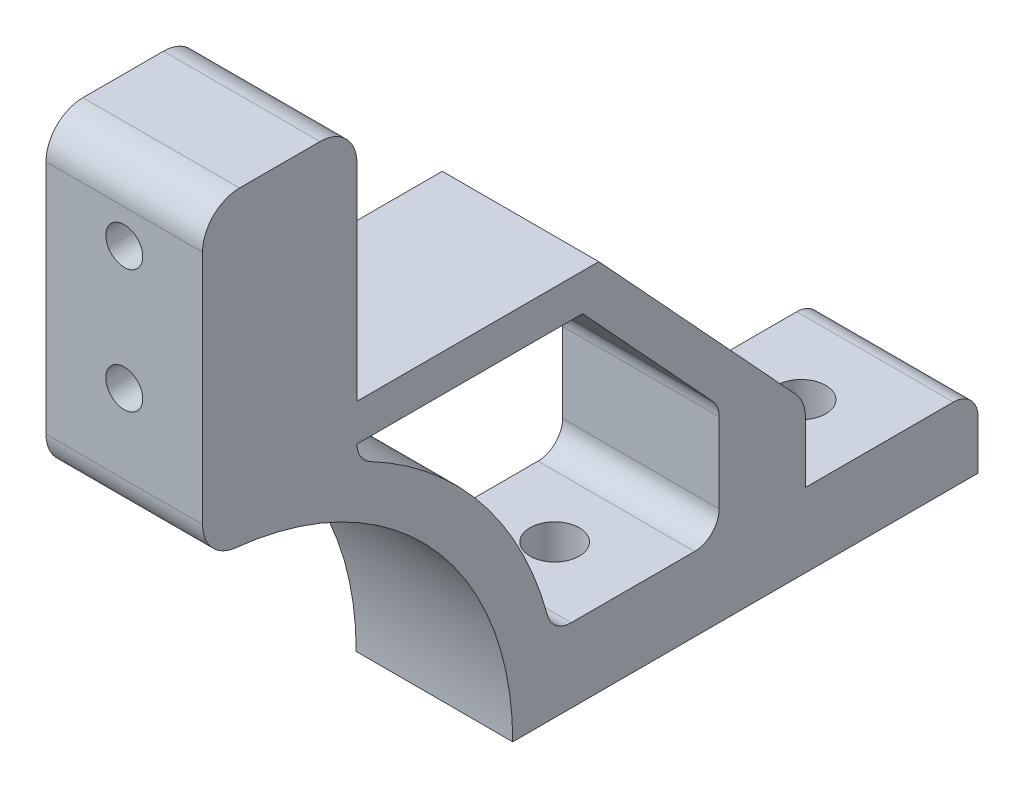
SolidWorks part; units mm, degrees
ref_plane "Front Plane" through (0, 0, 0) normal (0, 0, 1) x (1, 0, 0)
ref_plane "Top Plane" through (0, 0, 0) normal (0, 1, 0) x (1, 0, 0)
ref_plane "Right Plane" through (0, 0, 0) normal (1, 0, 0) x (0, 0, -1)
sketch "Sketch1" plane through (0, 0, 0) normal (1, 0, 0) x (0, 0, -1)
  line L0 (49.2041, 10.9568) -> (33.2349, 28.2516)
  line L3 (4.0847, 48) -> (10.6144, 48)
  line L4 (50, 4.0009) -> (50, 8.9217)
  line L11 (50, 4.0009) -> (62, 4.0009)
  line L16 (64, 2.0009) -> (64, -1.9991)
  line L18 (26.2541, -1.9991) -> (64, -1.9991)
  line L19 (42.4694, 13.8283) -> (31.9216, 25.2516)
  line L20 (13.6144, 39.9642) -> (13.6144, 28.2516)
  line L21 (43, 12.4715) -> (43, 6.0009)
  line L22 (41, 4.0009) -> (31, 4.0009)
  line L23 (1.0847, 25.8574) -> (1.0847, 45)
  line L24 (13.6144, 39.9642) -> (13.6144, 45)
  line L25 (13.6144, 25.2516) -> (31.9216, 25.2516)
  line L26 (13.6144, 28.2516) -> (33.2349, 28.2516)
  arc A0 (3.7814, 22.8728) -> (26.2541, -1.9991) centre (1.2541, -1.9991) cw
  arc A5 (29.0686, 5.4814) -> (14.682, 23.4822) centre (1.2541, -1.9991) ccw
  arc A6 (42.4694, 13.8283) -> (43, 12.4715) centre (41, 12.4715) cw
  arc A7 (43, 6.0009) -> (41, 4.0009) centre (41, 6.0009) cw
  arc A8 (31, 4.0009) -> (29.0686, 5.4814) centre (31, 6.0009) cw
  arc A9 (13.6144, 25.2516) -> (14.682, 23.4822) centre (15.6144, 25.2516) ccw
  arc A11 (62, 4.0009) -> (64, 2.0009) centre (62, 2.0009) cw
  arc A12 (49.2041, 10.9568) -> (50, 8.9217) centre (47, 8.9217) cw
  arc A14 (3.7814, 22.8728) -> (1.0847, 25.8574) centre (4.0847, 25.8574) cw
  arc A15 (13.6144, 45) -> (10.6144, 48) centre (10.6144, 45) ccw
  arc A16 (1.0847, 45) -> (4.0847, 48) centre (4.0847, 45) cw
  point P1 (56, 4.0009)
  point P29 (64, 4.0009)
  point P30 (36, 4.0009)
  point P33 (64, 4.0009)
  dimension "D7" = 25
  dimension "D5" = 6
  dimension "D6" = 3
  dimension "D9" = 20
  dimension "D8" = 2
  dimension "D12" = 3
  dimension "D4" = 3
  dimension "D2" = 3
  dimension "D3" = 14
  dimension "D10" = 5
  dimension "D11" = 5
  dimension "D14" = 6
extrude "Boss-Extrude2" add sketch "Sketch1" along normal blind 12.7
sketch "Croquis3" plane through (0, 4.0009, 0) normal (0, 1, 0) x (1, 0, 0)
  line L0 (12.7, 62) -> (0, 62) construction
  line L2 (0, 62) -> (0, 50) construction
  circle A0 centre (6.35, 56) radius 2
  circle A1 centre (6.35, 36) radius 2
  dimension "D1" = 6
  dimension "D2" = 6.35
  dimension "D3" = 20
extrude "Cortar-Extruir2" cut sketch "Croquis3" against normal blind 25
ref_plane "Plano1" through (12.7, 28.2516, -13.6144) normal (0, -1, 0) x (-1, 0, 0)
sketch "Croquis5" plane through (0, 0, -13.6144) normal (0, 0, -1) x (-1, 0, 0)
  line L0 (-12.7, 45) -> (-12.7, 28.2516) construction
  line L2 (-12.7, 28.2516) -> (0, 28.2516) construction
  circle A0 centre (-6.35, 32.2516) radius 1.5
  circle A1 centre (-6.35, 42.2516) radius 1.5
  dimension "D1" = 6.35
  dimension "D2" = 4
  dimension "D3" = 10
extrude "Cortar-Extruir3" cut sketch "Croquis5" against normal blind 17
